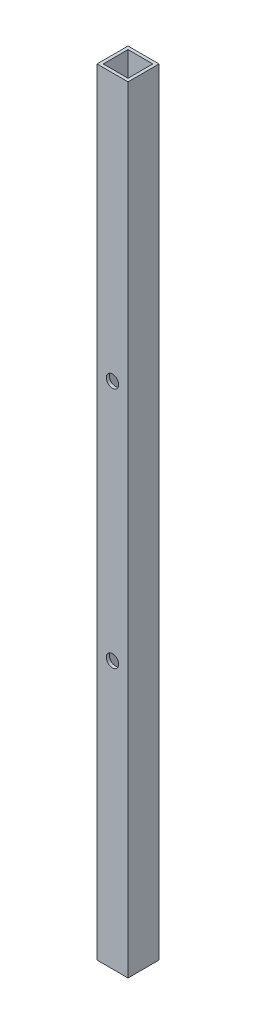
SolidWorks part; units mm, degrees
ref_plane "前视基准面" through (0, 0, 0) normal (0, 0, 1) x (1, 0, 0)
ref_plane "上视基准面" through (0, 0, 0) normal (0, 1, 0) x (1, 0, 0)
ref_plane "右视基准面" through (0, 0, 0) normal (1, 0, 0) x (0, 0, -1)
sketch "草图1" plane through (0, 0, 0) normal (0, 1, 0) x (1, 0, 0)
  line L1 (-5, 5) -> (5, 5)
  line L2 (-5, 5) -> (-5, -5)
  line L3 (-5, -5) -> (5, -5)
  line L4 (5, 5) -> (5, -5)
  line L5 (-5, 5) -> (5, -5) construction
  line L6 (-5, -5) -> (5, 5) construction
  line L7 (-4, 4) -> (4, 4)
  line L8 (-4, 4) -> (-4, -4)
  line L9 (-4, -4) -> (4, -4)
  line L10 (4, 4) -> (4, -4)
  line L11 (-4, 4) -> (4, -4) construction
  line L12 (-4, -4) -> (4, 4) construction
  point P0 (0, 0)
  point P6 (0, 0)
extrude "凸台-拉伸1" add sketch "草图1" along normal blind 250
ref_plane "基准面1" through (0, 125, 0) normal (0, 1, 0) x (1, 0, 0)
hole_wizard "Ø4.0 (4) 直径孔1" positions "草图3" profile "草图2" hole size "Ø4.0" standard "GB" end condition through all
sketch "草图3" plane through (0, 0, -5) normal (0, 0, -1) x (-1, 0, 0)
  line L0 (0, 164) -> (0, 250)
  line L1 (-5, 250) -> (5, 250) construction
  point P0 (0, 164)
sketch "草图2" plane through (0, 164, -5) normal (1, 0, 0) x (0, 1, 0)
  line L0 (0, 0) -> (0, 10)
  line L1 (0, 10) -> (2, 10)
  line L2 (2, 10) -> (2, 0)
  line L5 (2, 0) -> (0, 0)
  line L11 (0, -6.35) -> (0, 107.95) construction
  dimension "通孔孔直径" = 4
  dimension "通孔孔深度" = 10
mirror "镜向1" about plane through (0, 125, 0) normal (0, 1, 0) of "Ø4.0 (4) 直径孔1"
